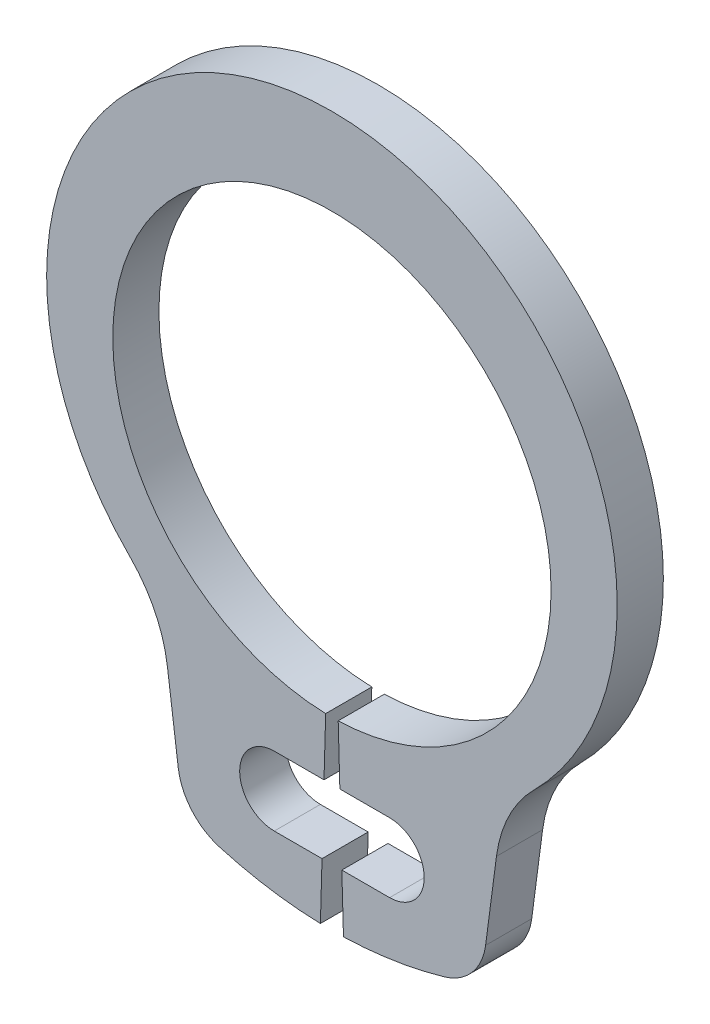
SolidWorks part; units mm, degrees
ref_plane "Plane1" through (0, 0, 0) normal (0, 0, 1) x (1, 0, 0)
ref_plane "Plane2" through (0, 0, 0) normal (0, 1, 0) x (1, 0, 0)
ref_plane "Plane3" through (0, 0, 0) normal (1, 0, 0) x (0, 0, -1)
sketch "Clipboard" plane through (0, 0, 0) normal (0, 0, 1) x (1, 0, 0)
  line L0 (0, 0) -> (1.5, 0)
  line L1 (0, 0) -> (0, 0.9)
  line L2 (0, 0) -> (0, -3.2)
  circle A0 centre (0, 0) radius 0.6
  circle A1 centre (0, 0) radius 4
  dimension "HoleDia" = 1.2
  dimension "ShaftDia" = 8
  dimension "LargeSection" = 1.5
  dimension "SmallSection" = 0.9
  dimension "LugSection" = 3.2
sketch "BodySke" plane through (0, 0, 0) normal (0, 0, 1) x (1, 0, 0)
  line L0 (-1.5431, 0) -> (1.5431, 0) construction
  line L1 (0, 0) -> (0, 5.3) construction
  line L2 (0.1086, -3.7984) -> (0.2, -6.9971)
  line L3 (-0.1086, -3.7984) -> (-0.2, -6.9971)
  line L4 (0, 0) -> (5.1312, -4.7614) construction
  line L5 (0, 0) -> (-5.1312, -4.7614) construction
  line L7 (2.853, -4.4615) -> (2.6646, -5.8925)
  line L8 (-2.853, -4.4615) -> (-2.6646, -5.8925)
  circle A0 centre (0, 0) radius 3.8 construction
  arc A1 (0.1086, -3.7984) -> (-0.1086, -3.7984) centre (0, 0) ccw
  arc A2 (3.4452, -3.1969) -> (-3.4452, -3.1969) centre (0, 0.3531) ccw construction
  arc A3 (0.2, -6.9971) -> (1.952, -6.7223) centre (0, 0) ccw
  arc A4 (3.5037, -3.1392) -> (2.853, -4.4615) centre (5.1312, -4.7614) ccw
  arc A5 (-2.853, -4.4615) -> (-3.5037, -3.1392) centre (-5.1312, -4.7614) ccw
  arc A6 (-1.952, -6.7223) -> (-0.2, -6.9971) centre (0, 0) ccw
  arc A7 (3.5037, -3.1392) -> (-3.5037, -3.1392) centre (0, 0.3531) ccw
  arc A8 (-2.8186, -4.7229) -> (2.8186, -4.7229) centre (0, 0) ccw construction
  circle A9 centre (1, -5.4083) radius 0.6
  circle A10 centre (-1, -5.4083) radius 0.6
  arc A11 (2.6646, -5.8925) -> (1.952, -6.7223) centre (1.6731, -5.762) cw
  arc A12 (-2.6646, -5.8925) -> (-1.952, -6.7223) centre (-1.6731, -5.762) ccw
  point P28 (2.5839, -6.5057)
  point P31 (-2.5839, -6.5057)
  dimension "HoleDia" = 1.2
  dimension "GrooveDia" = 7.6
  dimension "LugRad" = 7
  dimension "HoleOffsetRad" = 5.5
  dimension "D3" = 1
  dimension "LargeRad" = 5.3
  dimension "SmallRad" = 4.7
  dimension "SmallAngle" = 94.281
  dimension "D2" = 15
  dimension "HoleSpacing" = 2
  dimension "Gap" = 0.4
extrude "Body" add sketch "BodySke" against normal blind 0.8
sketch "NotSke" plane through (0, 0, 0) normal (0, 0, 1) x (1, 0, 0)
  line L0 (1, -4.8083) -> (1, -6.0083)
  line L1 (1, -6.0083) -> (-1, -6.0083)
  line L2 (-1, -6.0083) -> (-1, -4.8083)
  line L3 (-1, -4.8083) -> (1, -4.8083)
  circle A0 centre (1, -5.4083) radius 0.6 construction
  circle A1 centre (-1, -5.4083) radius 0.6 construction
extrude "Notch" cut sketch "NotSke" against normal through all
sketch "UnlSke" plane through (0, 0, 0) normal (0, 0, 1) x (1, 0, 0)
  line L0 (1.952, -3.2603) -> (1.952, -6.7223)
  line L1 (-1.952, -3.2603) -> (-1.952, -6.7223)
  arc A0 (1.952, -3.2603) -> (-1.952, -3.2603) centre (0, 0) ccw
  arc A1 (1.952, -6.7223) -> (-1.952, -6.7223) centre (0, 0) ccw
  arc A4 (-1.952, -6.7223) -> (-0.2, -6.9971) centre (0, 0) ccw construction
  arc A5 (0.1086, -3.7984) -> (-0.1086, -3.7984) centre (0, 0) ccw construction
extrude "Unlug" [suppressed] add sketch "UnlSke" against normal through all
equation "' \"ShaftDia@Clipboard\" = 3"
equation "' \"Thickness@Body\" = 0.4"
equation "' \"GrooveDia@BodySke\" = 2.8"
equation "' \"LugSection@Clipboard\" = 1.9"
equation "' \"LargeSection@Clipboard\" = 0.8"
equation "' \"HoleDia@Clipboard\" = 0.8"
equation "' \"ShaftDia@Clipboard\" = 9"
equation "' \"Thickness@Body\" = 1"
equation "' \"GrooveDia@BodySke\" = 8.6"
equation "' \"LugSection@Clipboard\" = 3.3"
equation "' \"LargeSection@Clipboard\" = 1.7"
equation "' \"HoleDia@Clipboard\" = 1.2"
equation "\"SmallSection@Clipboard\" =  \"LargeSection@Clipboard\" * 0.6"
equation "\"Gap@BodySke\" =  \"Thickness@Body\" / 2"
equation "\"LargeRad@BodySke\" =  \"GrooveDia@BodySke\" / 2 +  \"LargeSection@Clipboard\""
equation "\"SmallRad@BodySke\" =  \"GrooveDia@BodySke\" / 2 +  \"SmallSection@Clipboard\""
equation "\"LugRad@BodySke\" = \"GrooveDia@BodySke\" / 2 + \"LugSection@Clipboard\""
equation "\"HoleOffsetRad@BodySke\" = (  \"ShaftDia@Clipboard\" / 2 + \"LugRad@BodySke\" ) / 2"
equation "\"HoleSpacing@BodySke\" = \"Gap@BodySke\"  * 2 +  \"HoleDia@Clipboard\""
equation "\"HoleDia@BodySke\" =  \"HoleDia@Clipboard\""
equation "\"SmallAngle@BodySke\" = atn(\"HoleSpacing@BodySke\" / 2 / sqr(\"HoleOffsetRad@BodySke\"  * \"HoleOffsetRad@BodySke\" - (\"HoleSpacing@BodySke\" / 2) * (\"HoleSpacing@BodySke\" / 2) ))  * 9 * ( 180 / 3.141593)"
